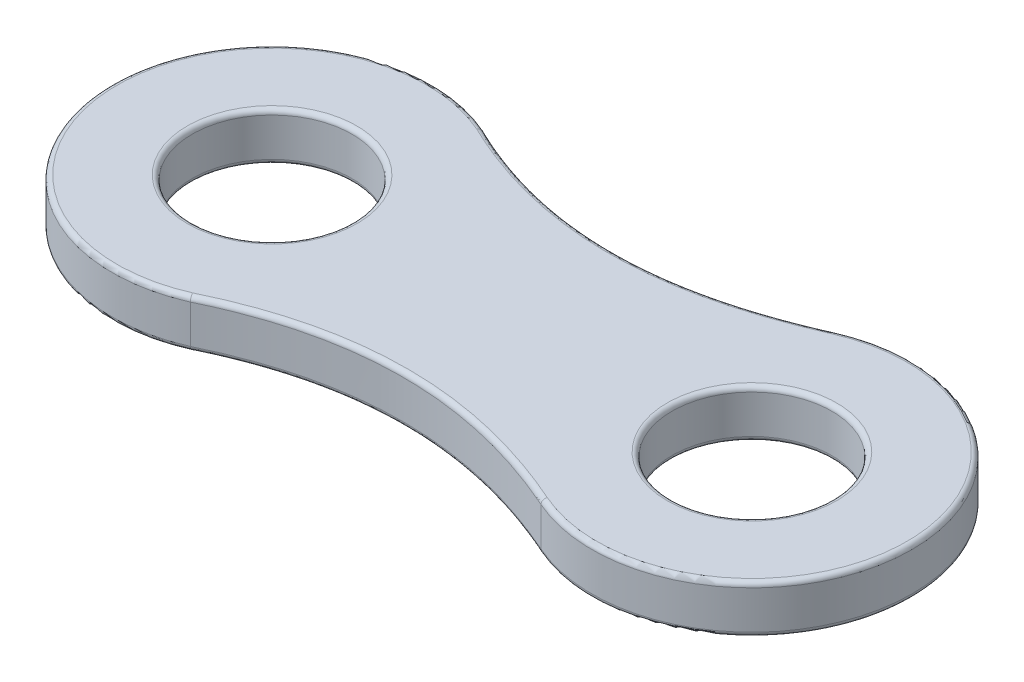
SolidWorks part; units mm, degrees
ref_plane "Front Plane" through (0, 0, 0) normal (0, 0, 1) x (1, 0, 0)
ref_plane "Top Plane" through (0, 0, 0) normal (0, 1, 0) x (1, 0, 0)
ref_plane "Right Plane" through (0, 0, 0) normal (1, 0, 0) x (0, 0, -1)
sketch "Sketch1" plane through (0, 0, 0) normal (0, 1, 0) x (1, 0, 0)
  line L1 (-1.25, 0.5) -> (1.25, 0.5) construction
  line L2 (-1.25, 0.5) -> (-1.25, -0.5) construction
  line L3 (-1.25, -0.5) -> (1.25, -0.5) construction
  line L4 (1.25, 0.5) -> (1.25, -0.5) construction
  line L5 (-1.25, 0.5) -> (1.25, -0.5) construction
  line L6 (-1.25, -0.5) -> (1.25, 0.5) construction
  point P0 (0, 0)
  dimension "D1" = 2.5
  dimension "D2" = 1
sketch "Sketch2" plane through (0, 0, 0) normal (0, 1, 0) x (1, 0, 0)
  line L0 (-1.25, 0.5) -> (-1.25, -0.5) construction
  line L1 (1.25, 0.5) -> (1.25, -0.5) construction
  line L2 (-0.75, 0) -> (0.75, 0) construction
  arc A0 (-0.5481, 0.4574) -> (-0.5481, -0.4574) centre (-0.75, 0) ccw
  arc A1 (0.5481, -0.4574) -> (0.5481, 0.4574) centre (0.75, 0) ccw
  circle A2 centre (-0.75, 0) radius 0.25
  circle A3 centre (0.75, 0) radius 0.25
  spline S0 degree 3 poles (-0.5481, 0.4574) (-0.161, 0.2696) (0.1963, 0.3021) (0.5481, 0.4574) knots 0 0 0 0 1 1 1 1
  spline S1 degree 3 poles (-0.5481, -0.4574) (-0.161, -0.2696) (0.1963, -0.3021) (0.5481, -0.4574) knots 0 0 0 0 1 1 1 1
  dimension "D1" = 1
  dimension "D2" = 0.5
extrude "Boss-Extrude1" add sketch "Sketch2" along normal blind 0.15
fillet "Fillet1" radius 0.015 12 edges at (0.75, 0, 0.25) (-0.75, 0, 0.25) (1.25, 0, 0) (-1.25, 0, 0) (0.75, 0.15, 0.25) (-1.25, 0.15, 0) (1.25, 0.15, 0) (-0.75, 0.15, 0.25)
